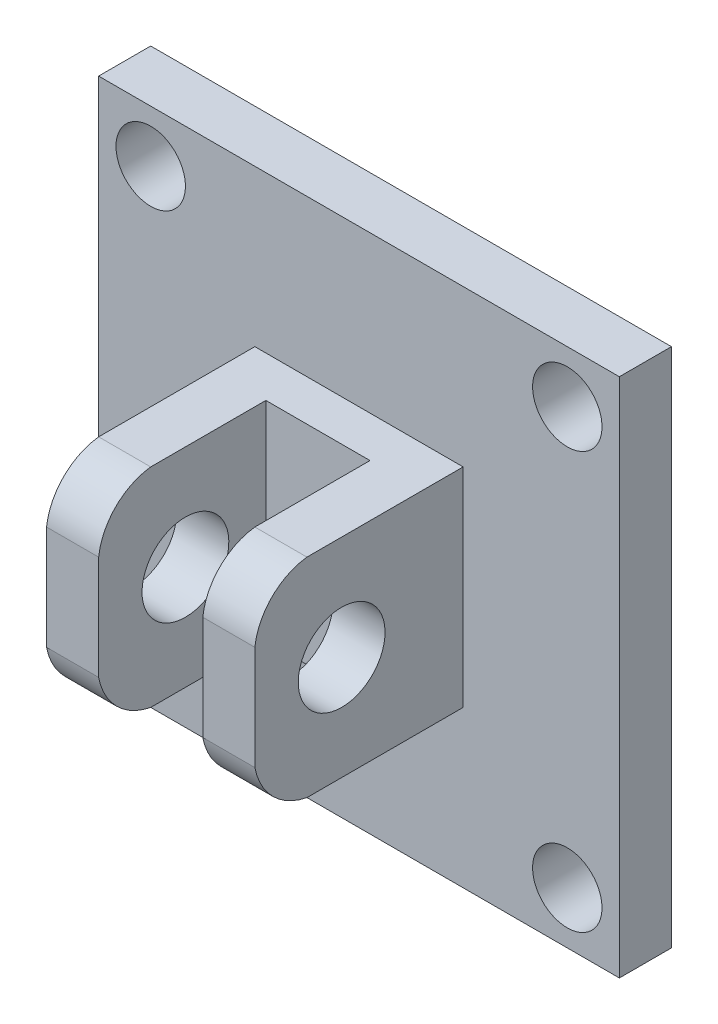
SolidWorks part; units mm, degrees
ref_plane "Front Plane" through (0, 0, 0) normal (0, 0, 1) x (1, 0, 0)
ref_plane "Top Plane" through (0, 0, 0) normal (0, 1, 0) x (1, 0, 0)
ref_plane "Right Plane" through (0, 0, 0) normal (1, 0, 0) x (0, 0, -1)
sketch "Esquisse1" plane through (0, 0, 0) normal (0, 0, 1) x (1, 0, 0)
  line L1 (0, 0) -> (12, 0)
  line L2 (0, 0) -> (0, -12)
  line L3 (0, -12) -> (12, -12)
  line L4 (12, 0) -> (12, -12)
  line L5 (0, 0) -> (12, -12) construction
  line L6 (0, -12) -> (12, 0) construction
  point P5 (6, -6)
  dimension "D1" = 12
  dimension "D2" = 12
extrude "Boss.-Extru.1" add sketch "Esquisse1" along normal blind 12
sketch "Esquisse2" plane through (0, 0, 0) normal (0, 1, 0) x (1, 0, 0)
  line L0 (12, -12) -> (0, -12) construction
  line L1 (3, -12) -> (9, -12)
  line L2 (3, -12) -> (3, -2.3658)
  line L3 (3, -2.3658) -> (9, -2.3658)
  line L4 (9, -12) -> (9, -2.3658)
  line L5 (3, -12) -> (9, -2.3658) construction
  line L6 (3, -2.3658) -> (9, -12) construction
  line L7 (12, 0) -> (0, 0) construction
  point P4 (6, -7.1829)
  point P7 (6, -2.3658)
  point P10 (6, 0)
  dimension "D1" = 6
extrude "Enlèv. mat.-Extru.1" cut sketch "Esquisse2" against normal through all
sketch "Esquisse3" plane through (0, 0, 0) normal (-1, 0, 0) x (0, 0, 1)
  line L0 (12, 0) -> (0, 0) construction
  line L1 (0, 0) -> (0, -12) construction
  line L2 (12, 0) -> (12, -12) construction
  line L3 (12, -12) -> (0, -12) construction
  line L4 (12, -12) -> (9, -12)
  line L5 (12, 0) -> (12, -3)
  line L6 (12, 0) -> (9, 0)
  line L7 (12, -9) -> (12, -12)
  circle A0 centre (7, -6) radius 2.5
  arc A1 (9, 0) -> (12, -3) centre (8.5954, -3.4046) cw
  arc A3 (12, -9) -> (9, -12) centre (8.2868, -8.2868) cw
  point P7 (0, -6)
  dimension "D1" = 5
  dimension "D2" = 3
  dimension "D3" = 3
  dimension "D4" = 3
  dimension "D5" = 5
extrude "Enlèv. mat.-Extru.2" cut sketch "Esquisse3" against normal through all
sketch "Esquisse4" plane through (0, 0, 0) normal (0, 0, -1) x (-1, 0, 0)
  line L0 (-12, 0) -> (0, 0) construction
  line L1 (-21, 9) -> (9, 9)
  line L2 (-21, 9) -> (-21, -21)
  line L3 (-21, -21) -> (9, -21)
  line L4 (9, 9) -> (9, -21)
  line L5 (-21, 9) -> (9, -21) construction
  line L6 (-21, -21) -> (9, 9) construction
  line L7 (-12, -12) -> (-12, 0) construction
  circle A0 centre (-18, 6) radius 2
  circle A1 centre (6, 6) radius 2
  circle A2 centre (-18, -18) radius 2
  circle A3 centre (6, -18) radius 2
  point P4 (-6, -6)
  point P7 (-6, 0)
  point P10 (-12, -6)
  dimension "D4" = 4
  dimension "D5" = 4
  dimension "D6" = 4
  dimension "D7" = 4
  dimension "D1" = 30
  dimension "D2" = 30
  dimension "D3" = 3
  dimension "D8" = 3
  dimension "D9" = 3
  dimension "D10" = 3
extrude "Boss.-Extru.2" add sketch "Esquisse4" along normal blind 3
